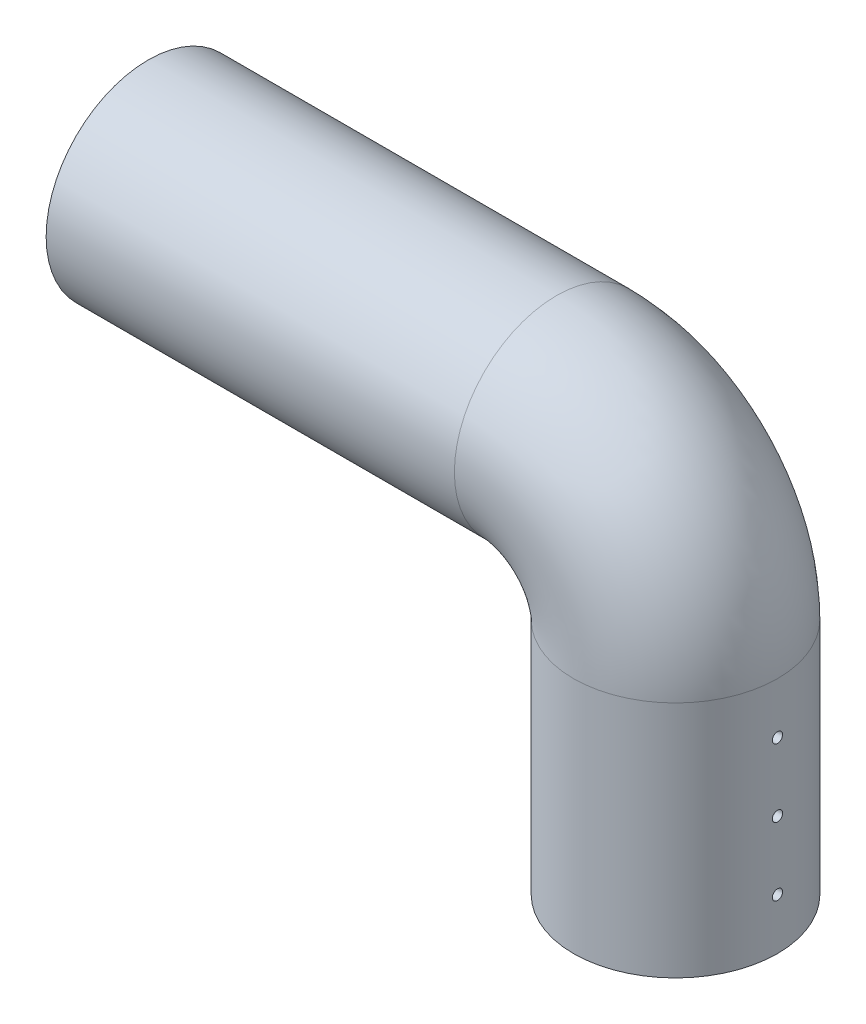
SolidWorks part; units mm, degrees
ref_plane "Front" through (0, 0, 0) normal (0, 0, 1) x (1, 0, 0)
ref_plane "Top" through (0, 0, 0) normal (0, 1, 0) x (1, 0, 0)
ref_plane "Right" through (0, 0, 0) normal (1, 0, 0) x (0, 0, -1)
sketch "Sketch1" plane through (0, 0, 0) normal (0, 0, 1) x (1, 0, 0)
  line L0 (34.9766, 0) -> (34.9766, 70)
  line L1 (50, 0) -> (-50, 0) construction
  line L2 (-0.0234, 105) -> (-120.0234, 105)
  arc A0 (34.9766, 70) -> (-0.0234, 105) centre (-0.0234, 70) ccw
sketch "Sketch2" plane through (0, 0, 0) normal (0, 1, 0) x (1, 0, 0)
  circle A0 centre (34.9766, 0) radius 30
sweep "Sweep1" add profiles "Sketch2" path "Sketch1"
shell "Shell15" thickness 9
sketch "Sketch4" plane through (0, 0, 0) normal (1, 0, 0) x (0, 0, -1)
  line L2 (0, 70) -> (0, 0) construction
  line L3 (-30, 70) -> (30, 70) construction
  circle A0 centre (0, 35) radius 1.5
  circle A1 centre (0, 55) radius 1.5
  circle A2 centre (0, 15) radius 1.5
  dimension "D1" = 70
  dimension "D2" = 15
  dimension "D3" = 20
  dimension "D4" = 20
  dimension "D5" = 15
extrude "Cut-Extrude2" cut sketch "Sketch4" against normal through all and the other way through all
